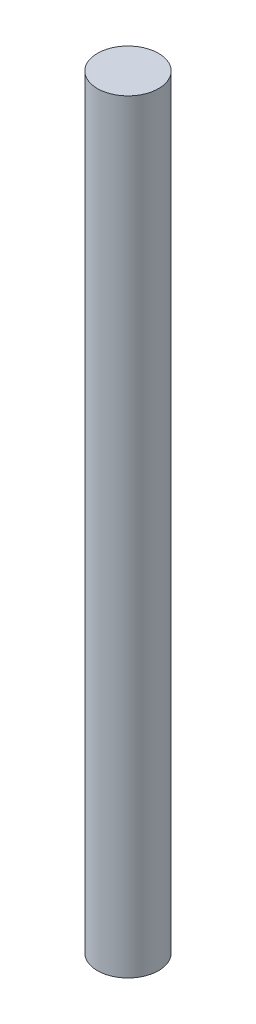
SolidWorks part; units mm, degrees
ref_plane "Спереди" through (0, 0, 0) normal (0, 0, 1) x (1, 0, 0)
ref_plane "Сверху" through (0, 0, 0) normal (0, 1, 0) x (1, 0, 0)
ref_plane "Справа" through (0, 0, 0) normal (1, 0, 0) x (0, 0, -1)
sketch "Sketch1" plane through (0, 0, 0) normal (0, 1, 0) x (1, 0, 0)
  circle A0 centre (0, 0) radius 4
  dimension "D1" = 8
extrude "Boss-Extrude1" add sketch "Sketch1" along normal blind 100
